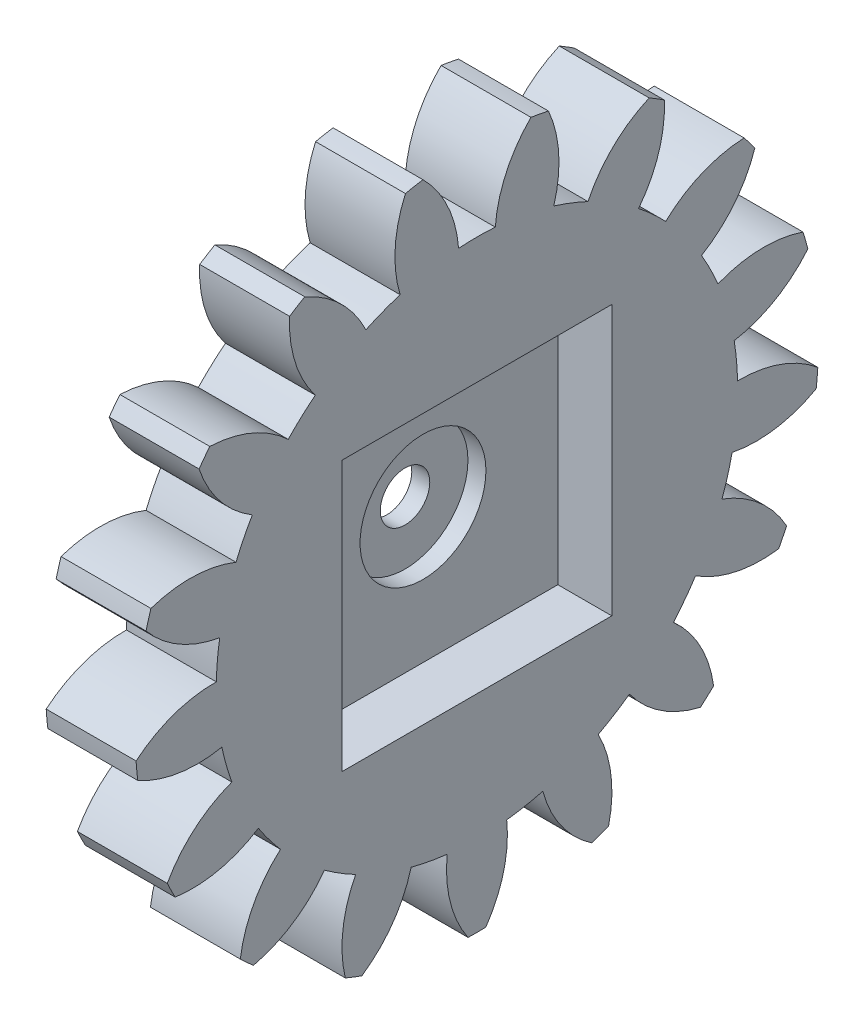
SolidWorks part; units mm, degrees
ref_plane "Plane1" through (0, 0, 0) normal (0, 0, 1) x (1, 0, 0)
ref_plane "Plane2" through (0, 0, 0) normal (0, 1, 0) x (1, 0, 0)
ref_plane "Plane3" through (0, 0, 0) normal (1, 0, 0) x (0, 0, -1)
sketch "HoldingSke" plane through (0, 0, 0) normal (0, 1, 0) x (1, 0, 0)
  line L0 (0, 0) -> (0.4782, -0.1462)
  line L1 (-15, 0) -> (100, 0) construction
  line L2 (0, 0) -> (-2.1039, 2.3779)
  line L3 (0, 0) -> (-11.863, 4.5341)
  line L4 (0, 0) -> (8.2586, 2.5249)
  line L5 (0, 0) -> (-46.8476, -17.4728)
  line L6 (0, 0) -> (-4.1448, -2.7965)
  line L7 (-2.1039, 2.3779) -> (8.6586, 51.2059)
  line L8 (-76.2, 54.61) -> (-75.9, 54.61)
  line L9 (-71.009, 38.7566) -> (-53.1078, 45.2721)
  line L10 (-76.2, 71.12) -> (104.1128, 71.12)
  line L11 (0, 0) -> (-5, 0)
  line L12 (-76.2, 101.6) -> (-76.133, 101.6)
  line L13 (24.9733, 27.94) -> (52.9518, 28.4284)
  line L14 (24.9733, 27.94) -> (24.9743, 27.94)
  line L15 (24.9733, 27.94) -> (100.4006, 29.5858)
  line L16 (-63.627, -2) -> (-12.827, -2)
  circle A0 centre (0, 0) radius 1
  circle A1 centre (0, 0) radius 14.499
  circle A2 centre (0, 0) radius 37.5
  circle A3 centre (0, 0) radius 1
  dimension "MHD" = 28.998
  dimension "Hub_dia" = 75
  dimension "Bore" = 2
  dimension "MBD" = 2
  dimension "Num_teeth" = 17
  dimension "Pitch_radius" = 180.3128
  dimension "Pitch" = 0.5
  dimension "Width" = 5
  dimension "Overall_len" = 50
  dimension "Show_teeth" = 17
  dimension "Thickness" = 5
  dimension "OAL" = 50.0001
  dimension "T_dim" = 0.3
  dimension "Ap" = 20
  dimension "H" = 19.05
  dimension "Backlash" = 0.067
  dimension "Addendum_fac" = 1
  dimension "Dedendum_fac" = 1.25
  dimension "Clearance_fac" = 0.25
  dimension "Dedendum_add" = 0.001
  dimension "Module" = 2
sketch "BasProSke" plane through (0, 0, 0) normal (0, 1, 0) x (1, 0, 0)
  line L0 (-10, 0) -> (60, 0) construction
  line L1 (0, 0) -> (0, 19)
  line L2 (0, 0) -> (5, 0)
  line L3 (5, 0) -> (5, 19)
  line L4 (5, 19) -> (0, 19)
  dimension "Diameter" = 38
  dimension "Thickness" = 5
revolve "Base-Revolve" add sketch "BasProSke" angle 360 about L0
sketch "TooCutSke" plane through (0, 0, 0) normal (1, 0, 0) x (0, 0, -1)
  line L1 (0, 0) -> (0, 107) construction
  line L2 (0, 0) -> (-1.6857, 16.9162) construction
  line L3 (0, 0) -> (-6.2247, 33.2991) construction
  line L4 (-1.6857, 16.9162) -> (-3.1123, 16.6495) construction
  arc A0 (1.0204, 14.4631) -> (-1.0204, 14.4631) centre (0, 0) ccw
  arc A1 (3.0261, 18.7832) -> (-3.0261, 18.7832) centre (0, 0) ccw
  circle A2 centre (0, 0) radius 17 construction
  circle A3 centre (0, 0) radius 15.9748 construction
  arc A4 (-1.0204, 14.4631) -> (-3.0261, 18.7832) centre (-7.8003, 13.9409) ccw
  arc A5 (3.0261, 18.7832) -> (1.0204, 14.4631) centre (7.8003, 13.9409) ccw
  dimension "Root_dia" = 28.998
  dimension "Overcut_dia" = 38.0508
  dimension "Pitch_dia" = 34
  dimension "Base_dia" = 31.9495
  dimension "Flank_rad" = 6.8
  dimension "Half_ang" = 10.588
  dimension "Half_CT" = 1.4513
extrude "ToothCut" cut sketch "TooCutSke" along normal through all
fillet "Breaks" [suppressed] radius 0.04
fillet "RootFillets" [suppressed] radius 0.501
pattern_circular "TeethCuts" count 17 every 21.176 about axis through (-10, 0, 0) along (1, 0, 0) of "ToothCut", "RootFillets", "Breaks"
sketch "HubNeaOneSke" plane through (0, 0, 0) normal (-1, 0, 0) x (0, 0, 1)
  circle A0 centre (0, 0) radius 14.499
  dimension "Diameter" = 28.998
extrude "HubNearOne" [suppressed] add sketch "HubNeaOneSke" along normal blind 45.0001
sketch "HubNeaBotSke" plane through (0, 0, 0) normal (-1, 0, 0) x (0, 0, 1)
  circle A0 centre (0, 0) radius 14.499
  dimension "Diameter" = 28.998
extrude "HubNearBoth" [suppressed] add sketch "HubNeaBotSke" along normal blind 22.5
ref_plane "FarPln" through (5, 0, 0) normal (1, 0, 0) x (0, 0, -1)
sketch "HubFarSke" plane through (5, 0, 0) normal (1, 0, 0) x (0, 0, -1)
  circle A0 centre (0, 0) radius 14.499
  dimension "Diameter" = 28.998
extrude "HubFar" [suppressed] add sketch "HubFarSke" along normal blind 22.5
sketch "BorSke" plane through (0, 0, 0) normal (1, 0, 0) x (0, 0, -1)
  circle A0 centre (0, 0) radius 1.375
  dimension "Diameter" = 2.75
extrude "Bore" cut sketch "BorSke" along normal mid plane 100.0001
sketch "KeySke" plane through (0, 0, 0) normal (1, 0, 0) x (0, 0, -1)
  line L0 (-0.4, 0) -> (-0.4, 1.3)
  line L1 (-0.4, 1.3) -> (0.4, 1.3)
  line L2 (0.4, 1.3) -> (0.4, 0)
  line L3 (0, 0) -> (0, 34) construction
  line L4 (-0.4, 0) -> (0.4, 0)
  dimension "Offset" = 1.3
  dimension "Width" = 0.8
extrude "Keyway" [suppressed] cut sketch "KeySke" along normal mid plane 100.0001
pattern_circular "Keyway2" [suppressed] count 2 every 90 about axis through (-10, 0, 0) along (1, 0, 0)
sketch "Sketch2" plane through (5, 0, 0) normal (1, 0, 0) x (0, 0, -1)
  circle A0 centre (0, 0) radius 3.5
  dimension "D1" = 7
extrude "Cut-Extrude2" cut sketch "Sketch2" against normal offset from surface (4 mm away) 1 up to face at (0, 0, 0)
sketch "Sketch1" plane through (5, 0, 0) normal (1, 0, 0) x (0, 0, -1)
  line L1 (-7.5, -7.5) -> (7.5, -7.5)
  line L2 (-7.5, -7.5) -> (-7.5, 7.5)
  line L3 (-7.5, 7.5) -> (7.5, 7.5)
  line L4 (7.5, -7.5) -> (7.5, 7.5)
  line L5 (-7.5, -7.5) -> (7.5, 7.5) construction
  line L6 (-7.5, 7.5) -> (7.5, -7.5) construction
  point P0 (0, 0)
  dimension "D1" = 15
  dimension "D2" = 15
extrude "Cut-Extrude1" cut sketch "Sketch1" against normal offset from surface (3 mm away) 1 up to face at (1, 0, -1.375)
equation "' \"Module@HoldingSke\" = 6.35"
equation "' \"Num_teeth@HoldingSke\" = 12"
equation "' \"Ap@HoldingSke\" =  20"
equation "' \"Width@HoldingSke\" = 0.5 * 25.4"
equation "' \"Hub_dia@HoldingSke\"= 1 * 25.4"
equation "' \"Overall_len@HoldingSke\" = 1.0 * 25.4"
equation "' \"Bore@HoldingSke\" = 0.75 * 25.4"
equation "' \"T_dim@HoldingSke\" = 0.1 * 25.4"
equation "' \"Width@KeySke\" = 0.25 * 25.4"
equation "' \"Show_teeth@HoldingSke\" = 13"
equation "' \"Backlash@HoldingSke\" = 0.009 * 25.4"
equation "' \"Addendum_fac@HoldingSke\" = 1.0"
equation "' \"Dedendum_fac@HoldingSke\" = 1.25"
equation "' \"Dedendum_add@HoldingSke\" = 0.00005 * 25.4"
equation "' \"Clearance_fac@HoldingSke\" = 0.25"
equation "\"Pitch@HoldingSke\" = 1 / \"Module@HoldingSke\""
equation "\"Overcut_dia@TooCutSke\" = (\"Num_teeth@HoldingSke\" + 2 * \"Addendum_fac@HoldingSke\") / \"Pitch@HoldingSke\" + 0.002 * 25.4"
equation "\"Pitch_dia@TooCutSke\" = \"Num_teeth@HoldingSke\" / \"Pitch@HoldingSke\""
equation "\"Base_dia@TooCutSke\" = \"Num_teeth@HoldingSke\" / \"Pitch@HoldingSke\" * cos((\"Ap@HoldingSke\"  * 3.14159265 / 180))"
equation "\"Root_dia@TooCutSke\" = (\"Num_teeth@HoldingSke\" + 2) / \"Pitch@HoldingSke\" - 2 * (\"Addendum_fac@HoldingSke\" + \"Dedendum_fac@HoldingSke\") / \"Pitch@HoldingSke\" - \"Dedendum_add@HoldingSke\" * 2"
equation "\"Half_ang@TooCutSke\" = 180 / \"Num_teeth@HoldingSke\""
equation "\"Half_CT@TooCutSke\" = \"Num_teeth@HoldingSke\" / \"Pitch@HoldingSke\" * sin((3.14159265 / 2 / \"Num_teeth@HoldingSke\")) / 2 - 7 * \"Backlash@HoldingSke\" / 4"
equation "\"Flank_rad@TooCutSke\" = \"Num_teeth@HoldingSke\" / \"Pitch@HoldingSke\" / 5"
equation "\"Radius@RootFillets\" = \"Clearance_fac@HoldingSke\" / \"Pitch@HoldingSke\" + \"Dedendum_add@HoldingSke\""
equation "\"Break_rad@Breaks\" = 0.02 / \"Pitch@HoldingSke\""
equation "\"Thickness@HoldingSke\" = \"Width@HoldingSke\""
equation "\"OAL@HoldingSke\" = \"Thickness@HoldingSke\""
equation "\"MHD@HoldingSke\" = (\"Num_teeth@HoldingSke\" + 2) / \"Pitch@HoldingSke\" - 2 * (\"Addendum_fac@HoldingSke\" + \"Dedendum_fac@HoldingSke\")  / \"Pitch@HoldingSke\" - \"Dedendum_add@HoldingSke\" * 2"
equation "\"MBD@HoldingSke\" = (\"Num_teeth@HoldingSke\" + 2) / \"Pitch@HoldingSke\" - 2 * (\"Addendum_fac@HoldingSke\" + \"Dedendum_fac@HoldingSke\")  / \"Pitch@HoldingSke\" - \"Dedendum_add@HoldingSke\" * 2 - 0.002 * 25.4"
equation "\"MHD@HoldingSke\" = ((sgn( \"MHD@HoldingSke\" - \"Hub_dia@HoldingSke\" )-1)*( \"MHD@HoldingSke\" - \"Hub_dia@HoldingSke\" ))/-2+ \"Hub_dia@HoldingSke\""
equation "\"MBD@HoldingSke\" = ((sgn( \"MBD@HoldingSke\" - \"Bore@HoldingSke\" )-1)*( \"MBD@HoldingSke\" - \"Bore@HoldingSke\" ))/-2+ \"Bore@HoldingSke\""
equation "\"OAL@HoldingSke\" = ((sgn( \"OAL@HoldingSke\" - \"Overall_len@HoldingSke\" )+1)*( \"OAL@HoldingSke\" - \"Overall_len@HoldingSke\" ))/2 + \"Overall_len@HoldingSke\" + 0.000002 * 25.4"
equation "\"Num_teeth@TeethCuts\" = int( \"Show_teeth@HoldingSke\" ) + 1"
equation "\"Num_teeth@TeethCuts\" = ((sgn( \"Num_teeth@TeethCuts\" - \"Num_teeth@HoldingSke\" )-1)*( \"Num_teeth@TeethCuts\" - \"Num_teeth@HoldingSke\" ))/-2+ \"Num_teeth@HoldingSke\""
equation "\"Num_teeth@TeethCuts\" = ((sgn( \"Num_teeth@TeethCuts\" - 2.0)+1)*( \"Num_teeth@TeethCuts\" - 2.0))/2 +2.0"
equation "\"Angle@TeethCuts\" = 360.0 / \"Num_teeth@HoldingSke\""
equation "\"Diameter@BasProSke\" = (\"Num_teeth@HoldingSke\" + 2 * \"Addendum_fac@HoldingSke\") / \"Pitch@HoldingSke\""
equation "\"Thickness@BasProSke\"  = \"Thickness@HoldingSke\""
equation "' \"Fillet_rad@BasProSke\" =  \"Thickness@HoldingSke\" * 0.05"
equation "\"MHD@HoldingSke\" = ((sgn( \"MHD@HoldingSke\" - \"Root_dia@TooCutSke\" )-1)*( \"MHD@HoldingSke\" - \"Root_dia@TooCutSke\" ))/-2+ \"Root_dia@TooCutSke\""
equation "\"Diameter@HubNeaOneSke\" = \"MHD@HoldingSke\""
equation "\"Length@HubNearOne\" = \"OAL@HoldingSke\" - \"Thickness@BasProSke\""
equation "\"Diameter@HubNeaBotSke\" = \"MHD@HoldingSke\""
equation "\"Length@HubNearBoth\" = ( \"OAL@HoldingSke\" - \"Thickness@BasProSke\" ) / 2.0"
equation "\"Thickness@FarPln\" = \"Thickness@BasProSke\""
equation "\"Diameter@HubFarSke\" = \"MHD@HoldingSke\""
equation "\"Length@HubFar\" = ( \"OAL@HoldingSke\" - \"Thickness@BasProSke\" ) / 2.0"
equation "\"D1@Bore\" = \"OAL@HoldingSke\" * 2.0"
equation "\"D1@Keyway\" = \"OAL@HoldingSke\" * 2.0"
equation "\"Offset@KeySke\" = \"T_dim@HoldingSke\" + \"MBD@HoldingSke\" / 2.0"
